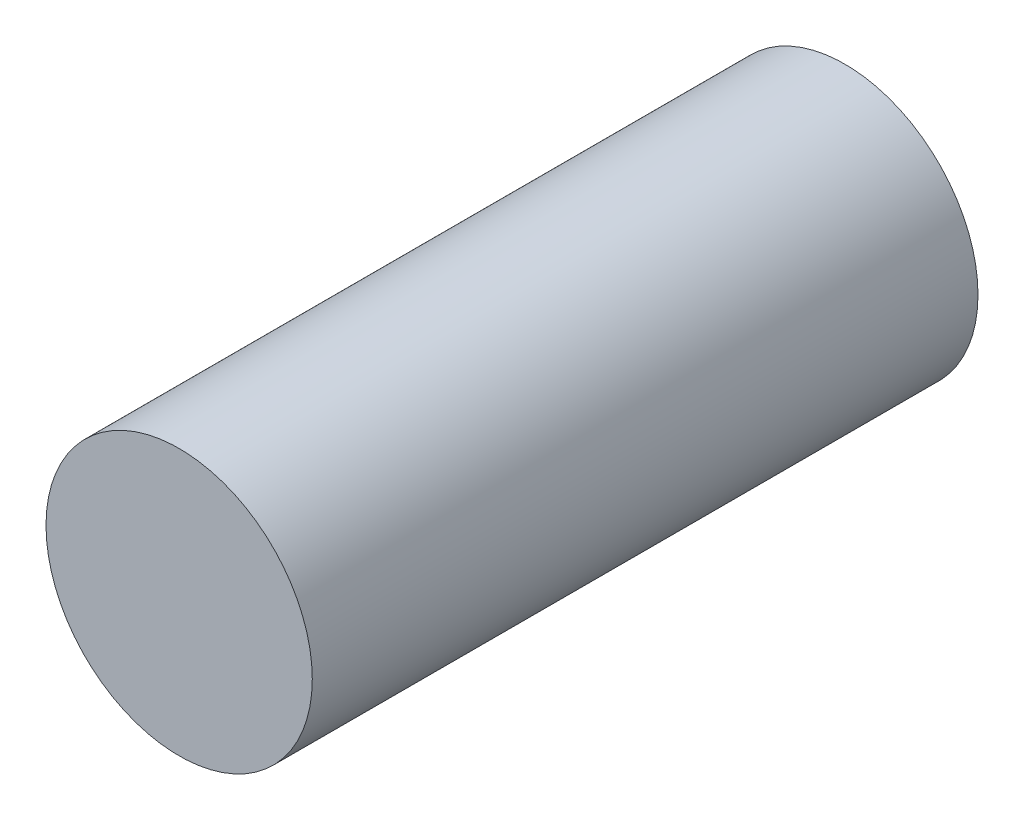
SolidWorks part; units mm, degrees
ref_plane "Front Plane" through (0, 0, 0) normal (0, 0, 1) x (1, 0, 0)
ref_plane "Top Plane" through (0, 0, 0) normal (0, 1, 0) x (1, 0, 0)
ref_plane "Right Plane" through (0, 0, 0) normal (1, 0, 0) x (0, 0, -1)
sketch "Sketch1" plane through (0, 0, 0) normal (0, 0, 1) x (1, 0, 0)
  circle A0 centre (0, 0) radius 3.175
  dimension "D1" = 6.35
extrude "Boss-Extrude1" add sketch "Sketch1" along normal blind 15.875
